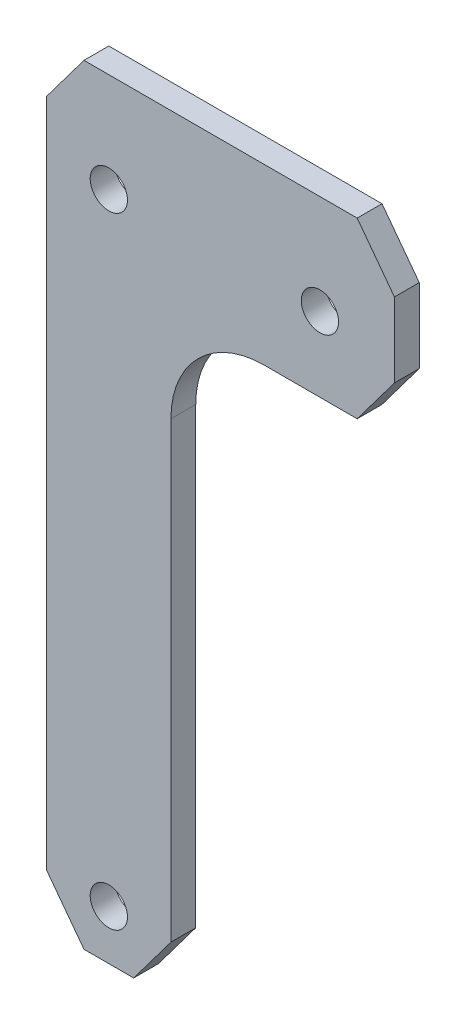
SolidWorks part; units mm, degrees
ref_plane "Piano frontale" through (0, 0, 0) normal (0, 0, 1) x (1, 0, 0)
ref_plane "Piano superiore" through (0, 0, 0) normal (0, 1, 0) x (1, 0, 0)
ref_plane "Piano destro" through (0, 0, 0) normal (1, 0, 0) x (0, 0, -1)
sketch "Schizzo1" plane through (0, 0, 0) normal (0, 0, 1) x (1, 0, 0)
  line L0 (0, 0) -> (0, -62)
  line L1 (0, -62) -> (10, -62)
  line L2 (10, -62) -> (10, -14)
  line L3 (10, -14) -> (28, -14)
  line L4 (28, -14) -> (28, 0)
  line L5 (28, 0) -> (0, 0)
  dimension "D1" = 10
  dimension "D2" = 62
  dimension "D3" = 14
  dimension "D4" = 28
extrude "Estrusione-Estrusione1" add sketch "Schizzo1" against normal blind 2 contours L5 L0 L1 L2 L3 L4
sketch "Schizzo2" plane through (0, 0, 0) normal (0, 0, 1) x (1, 0, 0)
  line L0 (3, 0) -> (14, 0)
  line L1 (0, 0) -> (0, -62) construction
  line L2 (14, 0) -> (14, -14) construction
  line L3 (10, -14) -> (28, -14) construction
  line L4 (28, 0) -> (0, 0) construction
  line L5 (14, 0) -> (25, 0)
  line L6 (3, 0) -> (0, -4)
  line L7 (25, 0) -> (28, -4)
  line L8 (28, -14) -> (28, 0) construction
  line L9 (0, -4) -> (0, 0)
  line L10 (0, 0) -> (3, 0)
  line L11 (25, 0) -> (28, 0)
  line L12 (28, 0) -> (28, -4)
  line L13 (5, -62) -> (5, 0) construction
  line L14 (0, -62) -> (10, -62) construction
  line L15 (3, -62) -> (0, -58)
  line L16 (0, -58) -> (10, -58) construction
  line L17 (10, -62) -> (10, -14) construction
  line L18 (7, -62) -> (10, -58)
  line L19 (0, -58) -> (0, -62)
  line L20 (0, -62) -> (3, -62)
  line L21 (7, -62) -> (10, -62)
  line L22 (10, -62) -> (10, -58)
  line L23 (28, -7) -> (0, -7) construction
  line L24 (25, -14) -> (28, -10)
  line L25 (28, -10) -> (28, -14)
  line L26 (28, -14) -> (25, -14)
  line L27 (25, -14) -> (28, -14)
  line L28 (28, -10) -> (25, -14)
  line M14 (28, 0) -> (0, 0)
  line M15 (0, 0) -> (0, -62)
  line M16 (0, -62) -> (10, -62)
  line M17 (10, -62) -> (10, -14)
  dimension "D1" = 11
  dimension "D2" = 3
  dimension "D3" = 2
  dimension "D5" = 5
  dimension "D6" = 3
extrude "Taglio-Estrusione1" cut sketch "Schizzo2" against normal through all contours L15 M16 M15 | L18 M16 M17 | L6 M14 M15 | L11 L12 L7 | L26 L24 L25
sketch "Schizzo3" plane through (0, 0, 0) normal (0, 0, 1) x (1, 0, 0)
  line L0 (28, -10) -> (28, -4) construction
  line L2 (3, -62) -> (7, -62) construction
  line L4 (5, -62) -> (5, 0) construction
  line L5 (25, 0) -> (3, 0) construction
  line L6 (0, -4) -> (0, -58) construction
  circle A0 centre (5, -8) radius 1.5
  circle A1 centre (22, -8) radius 1.5
  circle A2 centre (5, -58) radius 1.5
  dimension "D1" = 3
  dimension "D2" = 3
  dimension "D3" = 3
  dimension "D4" = 6
  dimension "D6" = 4
  dimension "D7" = 5
  dimension "D8" = 5
  dimension "D9" = 50
extrude "Taglio-Estrusione3" cut sketch "Schizzo3" against normal through all
sketch "Schizzo4" plane through (0, 0, 0) normal (0, 0, 1) x (1, 0, 0)
  line L0 (10, -58) -> (10, -14) construction
  line L1 (10, -14) -> (25, -14) construction
  line L2 (10, -21.5) -> (10, -14)
  line L3 (10, -14) -> (17.5, -14)
  arc A0 (17.5, -14) -> (10, -21.5) centre (17.5, -21.5) ccw
extrude "Estrusione-Estrusione2" add sketch "Schizzo4" against normal blind 2
